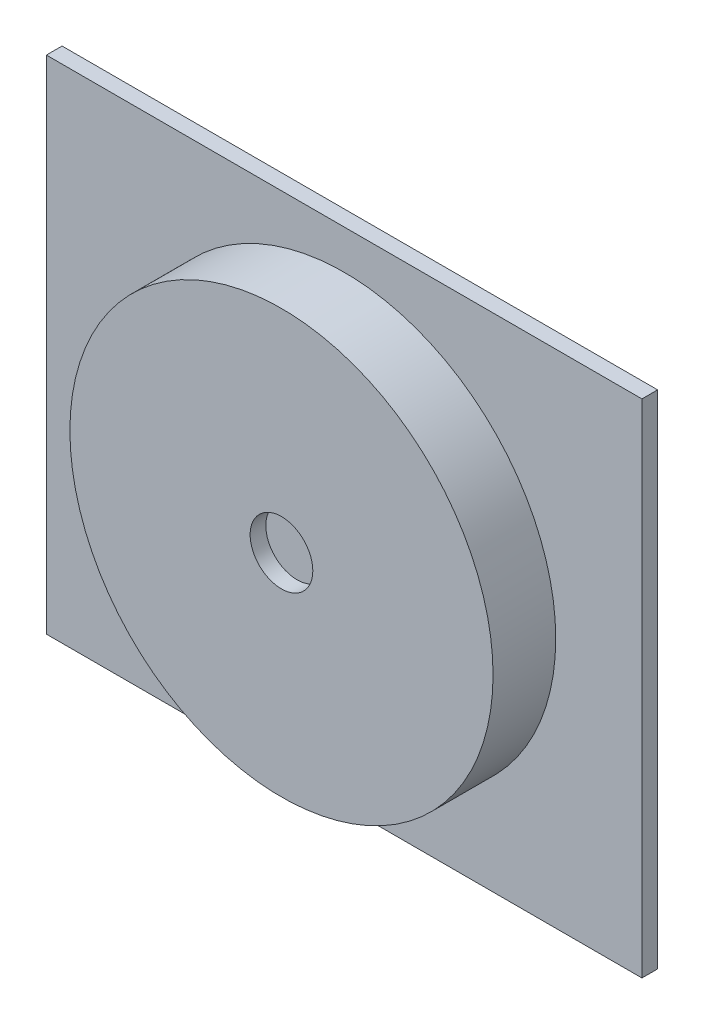
SolidWorks part; units mm, degrees
material "201 Annealed Stainless Steel (SS)"
ref_plane "Front Plane" through (0, 0, 0) normal (0, 0, 1) x (1, 0, 0)
ref_plane "Top Plane" through (0, 0, 0) normal (0, 1, 0) x (1, 0, 0)
ref_plane "Right Plane" through (0, 0, 0) normal (1, 0, 0) x (0, 0, -1)
sketch "Sketch1" plane through (0, 0, 0) normal (0, 0, 1) x (1, 0, 0)
  line L1 (-22.0558, 11.8973) -> (15.9442, 11.8973)
  line L2 (-22.0558, 11.8973) -> (-22.0558, -20.1027)
  line L3 (-22.0558, -20.1027) -> (15.9442, -20.1027)
  line L4 (15.9442, 11.8973) -> (15.9442, -20.1027)
  dimension "D1" = 38
  dimension "D2" = 32
extrude "Boss-Extrude1" add sketch "Sketch1" along normal blind 1
sketch "Sketch2" plane through (0, 0, 1) normal (0, 0, 1) x (1, 0, 0)
  line L0 (15.9442, -20.1027) -> (15.9442, 11.8973) construction
  line L1 (-22.0558, -20.1027) -> (15.9442, -20.1027) construction
  circle A0 centre (-3.0558, -4.1027) radius 13.5
  dimension "D1" = 19
  dimension "D3" = 27
  dimension "D2" = 16
extrude "Boss-Extrude2" add sketch "Sketch2" along normal blind 4
sketch "Sketch3" plane through (0, 0, 5) normal (0, 0, 1) x (1, 0, 0)
  circle A0 centre (-3.0558, -4.1027) radius 2
  circle A1 centre (-3.0558, -4.1027) radius 13.5 construction
  dimension "D1" = 4
  dimension "D2" = 0
extrude "Cut-Extrude1" cut sketch "Sketch3" against normal blind 1
